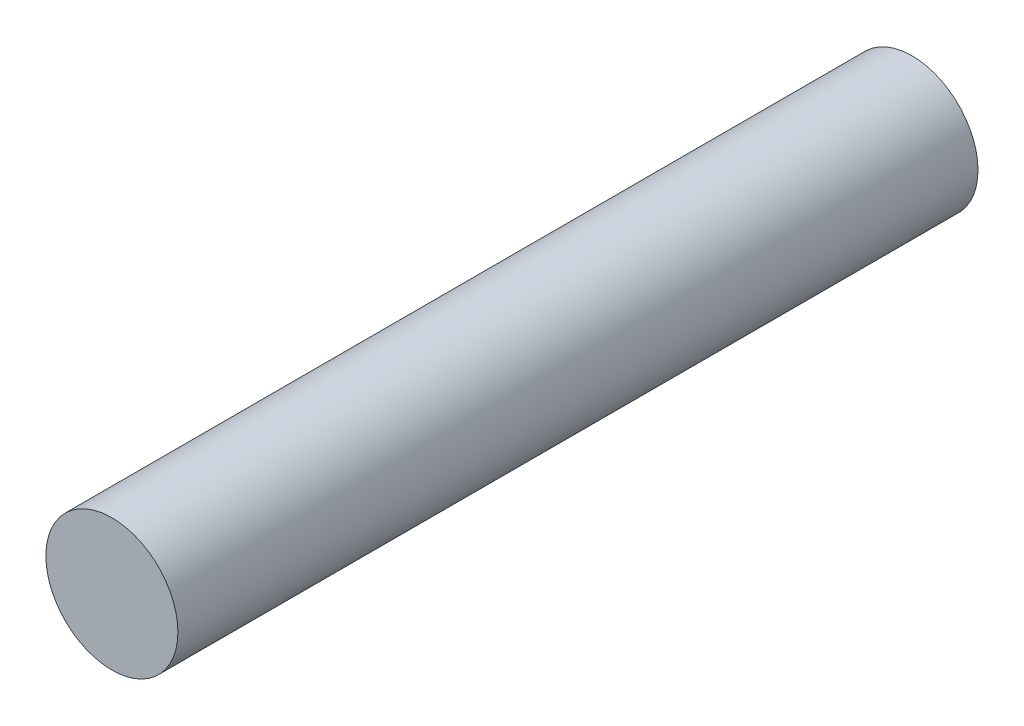
SolidWorks part; units mm, degrees
ref_plane "Ebene vorne" through (0, 0, 0) normal (0, 0, 1) x (1, 0, 0)
ref_plane "Ebene oben" through (0, 0, 0) normal (0, 1, 0) x (1, 0, 0)
ref_plane "Ebene rechts" through (0, 0, 0) normal (1, 0, 0) x (0, 0, -1)
sketch "Skizze1" plane through (0, 0, 0) normal (0, 0, 1) x (1, 0, 0)
  circle A0 centre (0, 0) radius 1.485
  dimension "D1" = 2.97
extrude "Aufsatz-Linear austragen1" add sketch "Skizze1" along normal blind 18
